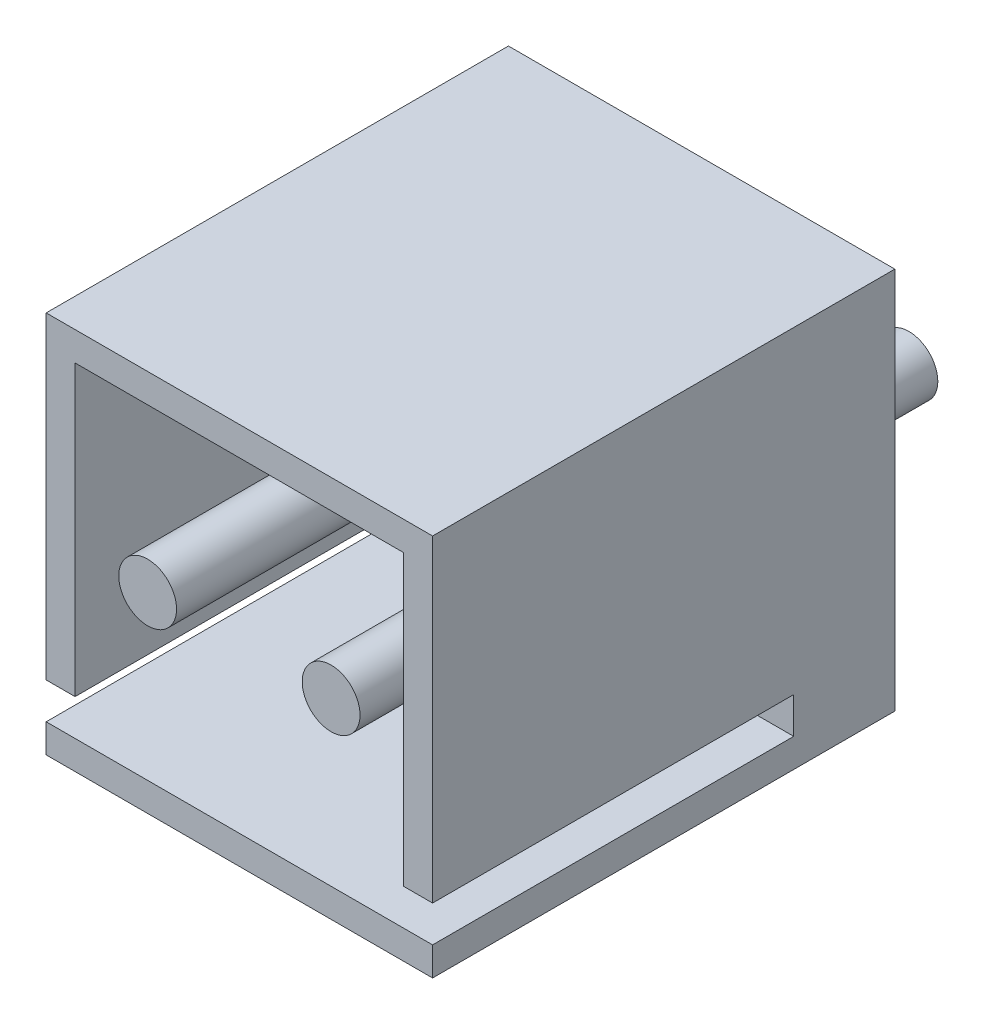
SolidWorks part; units mm, degrees
ref_plane "Спереди" through (0, 0, 0) normal (0, 0, 1) x (1, 0, 0)
ref_plane "Сверху" through (0, 0, 0) normal (0, 1, 0) x (1, 0, 0)
ref_plane "Справа" through (0, 0, 0) normal (1, 0, 0) x (0, 0, -1)
sketch "Эскиз1" plane through (0, 0, 0) normal (0, 0, 1) x (1, 0, 0)
  line L0 (0, 43.0382) -> (0, -41.0882) construction
  line L1 (-52.7879, 0) -> (56.1307, 0) construction
  line L3 (-2.675, 2.65) -> (2.675, 2.65)
  line L4 (-2.675, 2.65) -> (-2.675, -2.65)
  line L5 (-2.675, -2.65) -> (2.675, -2.65)
  line L6 (2.675, 2.65) -> (2.675, -2.65)
  dimension "D1" = 5.35
  dimension "D2" = 5.3
extrude "Вытянуть1" add sketch "Эскиз1" along normal blind 6.4
sketch "Эскиз2" plane through (0, 0, 6.4) normal (0, 0, 1) x (1, 0, 0)
  line L14 (-4.5773, 0) -> (3.2862, 0) construction
  line L15 (0, 1.6982) -> (0, -0.832) construction
  line L18 (-2.275, -2.25) -> (2.275, -2.25)
  line L19 (2.275, -2.25) -> (2.275, 2.25)
  line L20 (2.275, 2.25) -> (-2.275, 2.25)
  line L21 (-2.275, 2.25) -> (-2.275, -2.25)
  line L22 (-2.275, -2.25) -> (2.275, -2.25)
  line L23 (2.275, -2.25) -> (2.275, 2.25)
  line L24 (2.275, 2.25) -> (-2.275, 2.25)
  line L25 (-2.275, 2.25) -> (-2.275, -2.25)
  circle A0 centre (-1.27, 0) radius 0.4
  circle A1 centre (1.27, 0) radius 0.4
  dimension "D2" = 2.54
  dimension "D3" = 0.8
  dimension "D1" = 0.4
extrude "Вырез-Вытянуть1" cut sketch "Эскиз2" against normal blind 5
sketch "Эскиз3" plane through (0, 0, 6.4) normal (0, 0, 1) x (1, 0, 0)
  line L1 (-6.5166, -2.2528) -> (6.3828, -2.2528)
  line L2 (-6.5166, -2.2528) -> (-6.5166, -1.7514)
  line L3 (-6.5166, -1.7514) -> (6.3828, -1.7514)
  line L4 (6.3828, -2.2528) -> (6.3828, -1.7514)
extrude "Вырез-Вытянуть2" cut sketch "Эскиз3" against normal up to surface (5 mm away) up to face at (1.67, 0, 1.4)
sketch "Эскиз4" plane through (0, 0, 6.4) normal (0, 0, 1) x (1, 0, 0)
  circle A1 centre (-1.27, 0) radius 0.4
  circle A2 centre (-1.27, 0) radius 0.4
  circle A3 centre (1.27, 0) radius 0.4
  circle A4 centre (1.27, 0) radius 0.4
  dimension "D1" = 0
  dimension "D2" = 0
extrude "Вытянуть2" add sketch "Эскиз4" against normal blind 8
